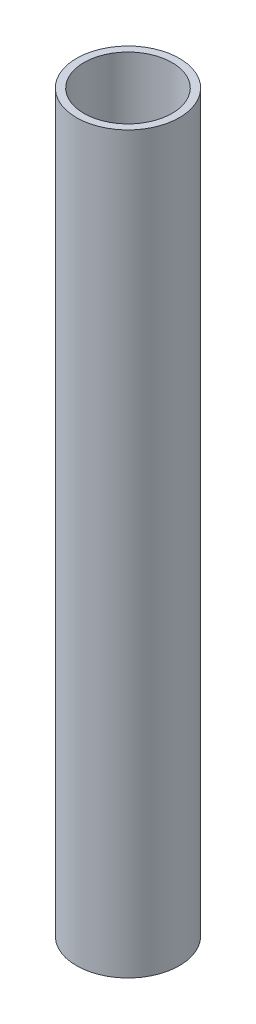
SolidWorks part; units mm, degrees
ref_plane "Front Plane" through (0, 0, 0) normal (0, 0, 1) x (1, 0, 0)
ref_plane "Top Plane" through (0, 0, 0) normal (0, 1, 0) x (1, 0, 0)
ref_plane "Right Plane" through (0, 0, 0) normal (1, 0, 0) x (0, 0, -1)
sketch "Sketch1" plane through (0, 0, 0) normal (0, 1, 0) x (1, 0, 0)
  circle A0 centre (0, 0) radius 3.5
  circle A1 centre (0, 0) radius 3
  dimension "D1" = 7
  dimension "D2" = 6
extrude "Boss-Extrude1" add sketch "Sketch1" along normal mid plane 50
